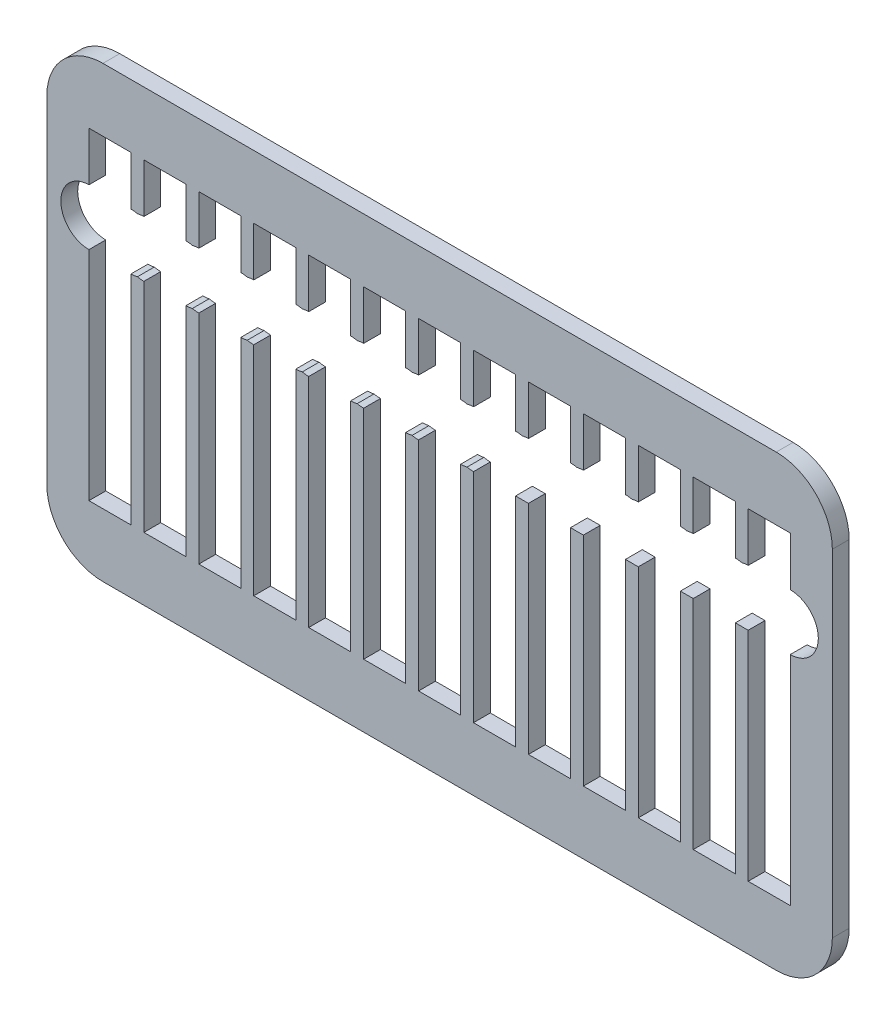
SolidWorks part; units mm, degrees
ref_plane "Front Plane" through (0, 0, 0) normal (0, 0, 1) x (1, 0, 0)
ref_plane "Top Plane" through (0, 0, 0) normal (0, 1, 0) x (1, 0, 0)
ref_plane "Right Plane" through (0, 0, 0) normal (1, 0, 0) x (0, 0, -1)
sketch "Sketch1" plane through (0, 0, 0) normal (0, 0, 1) x (1, 0, 0)
  line L1 (20, 0) -> (260, 0)
  line L2 (0, 20) -> (0, 140)
  line L3 (20, 160) -> (260, 160)
  line L4 (280, 20) -> (280, 140)
  arc A0 (260, 0) -> (280, 20) centre (260, 20) ccw
  arc A1 (260, 160) -> (280, 140) centre (260, 140) cw
  arc A2 (0, 140) -> (20, 160) centre (20, 140) cw
  arc A3 (20, 0) -> (0, 20) centre (20, 20) cw
  point P7 (280, 0)
  point P10 (280, 160)
  point P13 (0, 160)
  point P16 (0, 0)
  dimension "D3" = 20
  dimension "D1" = 280
  dimension "D2" = 160
extrude "Boss-Extrude1" add sketch "Sketch1" along normal blind 6
sketch "Sketch2" plane through (0, 0, 6) normal (0, 0, 1) x (1, 0, 0)
  line L0 (15, 137.5) -> (15, 160) construction
  line L1 (15, 137.5) -> (30, 137.5)
  line L2 (15, 137.5) -> (15, 120)
  line L3 (15, 22.5) -> (30, 22.5)
  line L4 (30, 137.5) -> (30, 120)
  line L5 (260, 160) -> (20, 160) construction
  line L6 (15, 22.5) -> (15, 0) construction
  line L7 (152.0833, 137.5) -> (152.0833, 120)
  line L8 (0, 110) -> (280, 110) construction
  line L9 (152.0833, 100) -> (152.0833, 22.5)
  line L10 (152.0833, 22.5) -> (167.0833, 22.5)
  line L11 (22.5, 22.5) -> (22.5, 37.2302) construction
  line L12 (15, 100) -> (15, 22.5)
  line L13 (30, 100) -> (30, 22.5)
  line L14 (34.5833, 137.5) -> (34.5833, 120)
  line L15 (34.5833, 100) -> (34.5833, 22.5)
  line L16 (34.5833, 22.5) -> (49.5833, 22.5)
  line L17 (49.5833, 100) -> (49.5833, 22.5)
  line L18 (49.5833, 137.5) -> (49.5833, 120)
  line L19 (34.5833, 137.5) -> (49.5833, 137.5)
  line L20 (54.1667, 137.5) -> (54.1667, 120)
  line L21 (54.1667, 100) -> (54.1667, 22.5)
  line L22 (54.1667, 22.5) -> (69.1667, 22.5)
  line L23 (69.1667, 100) -> (69.1667, 22.5)
  line L24 (69.1667, 137.5) -> (69.1667, 120)
  line L25 (54.1667, 137.5) -> (69.1667, 137.5)
  line L26 (73.75, 137.5) -> (73.75, 120)
  line L27 (73.75, 100) -> (73.75, 22.5)
  line L28 (73.75, 22.5) -> (88.75, 22.5)
  line L29 (88.75, 100) -> (88.75, 22.5)
  line L30 (88.75, 137.5) -> (88.75, 120)
  line L31 (73.75, 137.5) -> (88.75, 137.5)
  line L32 (93.3333, 137.5) -> (93.3333, 120)
  line L33 (93.3333, 100) -> (93.3333, 22.5)
  line L34 (93.3333, 22.5) -> (108.3333, 22.5)
  line L35 (108.3333, 100) -> (108.3333, 22.5)
  line L36 (108.3333, 137.5) -> (108.3333, 120)
  line L37 (93.3333, 137.5) -> (108.3333, 137.5)
  line L38 (112.9167, 137.5) -> (112.9167, 120)
  line L39 (112.9167, 100) -> (112.9167, 22.5)
  line L40 (112.9167, 22.5) -> (127.9167, 22.5)
  line L41 (127.9167, 100) -> (127.9167, 22.5)
  line L42 (127.9167, 137.5) -> (127.9167, 120)
  line L43 (112.9167, 137.5) -> (127.9167, 137.5)
  line L44 (132.5, 137.5) -> (132.5, 120)
  line L45 (132.5, 100) -> (132.5, 22.5)
  line L46 (132.5, 22.5) -> (147.5, 22.5)
  line L47 (147.5, 100) -> (147.5, 22.5)
  line L48 (147.5, 137.5) -> (147.5, 120)
  line L49 (132.5, 137.5) -> (147.5, 137.5)
  line L50 (15, 44.6954) -> (0, 44.6954) construction
  line L51 (0, 140) -> (0, 20) construction
  line L52 (280, 20) -> (280, 140) construction
  line L53 (167.0833, 100) -> (171.6667, 100)
  line L54 (167.0833, 100) -> (167.0833, 22.5)
  line L55 (167.0833, 137.5) -> (167.0833, 120)
  line L56 (152.0833, 137.5) -> (167.0833, 137.5)
  line L57 (171.6667, 137.5) -> (171.6667, 120)
  line L58 (171.6667, 100) -> (171.6667, 22.5)
  line L59 (171.6667, 22.5) -> (186.6667, 22.5)
  line L60 (186.6667, 100) -> (186.6667, 22.5)
  line L61 (186.6667, 137.5) -> (186.6667, 120)
  line L62 (171.6667, 137.5) -> (186.6667, 137.5)
  line L63 (191.25, 137.5) -> (191.25, 120)
  line L64 (191.25, 100) -> (191.25, 22.5)
  line L65 (191.25, 22.5) -> (206.25, 22.5)
  line L66 (206.25, 100) -> (206.25, 22.5)
  line L67 (206.25, 137.5) -> (206.25, 120)
  line L68 (191.25, 137.5) -> (206.25, 137.5)
  line L69 (210.8333, 137.5) -> (210.8333, 120)
  line L70 (210.8333, 100) -> (210.8333, 22.5)
  line L71 (210.8333, 22.5) -> (225.8333, 22.5)
  line L72 (225.8333, 100) -> (225.8333, 22.5)
  line L73 (225.8333, 137.5) -> (225.8333, 120)
  line L74 (210.8333, 137.5) -> (225.8333, 137.5)
  line L75 (230.4167, 137.5) -> (230.4167, 120)
  line L76 (230.4167, 100) -> (230.4167, 22.5)
  line L77 (230.4167, 22.5) -> (245.4167, 22.5)
  line L78 (245.4167, 100) -> (245.4167, 22.5)
  line L79 (245.4167, 137.5) -> (245.4167, 120)
  line L80 (230.4167, 137.5) -> (245.4167, 137.5)
  line L81 (250, 137.5) -> (250, 120)
  line L82 (250, 100) -> (250, 22.5)
  line L83 (250, 22.5) -> (265, 22.5)
  line L84 (265, 100) -> (265, 22.5)
  line L85 (265, 137.5) -> (265, 120)
  line L86 (250, 137.5) -> (265, 137.5)
  line L87 (186.6667, 100) -> (191.25, 100)
  line L88 (206.25, 100) -> (210.8333, 100)
  line L89 (225.8333, 100) -> (230.4167, 100)
  line L90 (245.4167, 100) -> (250, 100)
  arc A0 (30, 120) -> (32.2917, 119.7339) centre (30, 110) cw
  arc A1 (15, 120) -> (15, 100) centre (15, 110) ccw
  arc A2 (34.5833, 120) -> (32.2917, 119.7339) centre (34.5833, 110) ccw
  arc A3 (49.5833, 120) -> (51.875, 119.7339) centre (49.5833, 110) cw
  arc A4 (54.1667, 120) -> (51.875, 119.7339) centre (54.1667, 110) ccw
  arc A5 (69.1667, 120) -> (71.4583, 119.7339) centre (69.1667, 110) cw
  arc A6 (73.75, 120) -> (71.4583, 119.7339) centre (73.75, 110) ccw
  arc A7 (88.75, 120) -> (91.0417, 119.7339) centre (88.75, 110) cw
  arc A8 (93.3333, 120) -> (91.0417, 119.7339) centre (93.3333, 110) ccw
  arc A9 (108.3333, 120) -> (110.625, 119.7339) centre (108.3333, 110) cw
  arc A10 (112.9167, 120) -> (110.625, 119.7339) centre (112.9167, 110) ccw
  arc A11 (127.9167, 120) -> (130.2083, 119.7339) centre (127.9167, 110) cw
  arc A12 (132.5, 120) -> (130.2083, 119.7339) centre (132.5, 110) ccw
  arc A13 (147.5, 120) -> (149.7917, 119.7339) centre (147.5, 110) cw
  arc A14 (32.2917, 100.2661) -> (34.5833, 100) centre (34.5833, 110) ccw
  arc A15 (32.2917, 100.2661) -> (30, 100) centre (30, 110) cw
  arc A16 (51.875, 100.2661) -> (49.5833, 100) centre (49.5833, 110) cw
  arc A17 (51.875, 100.2661) -> (54.1667, 100) centre (54.1667, 110) ccw
  arc A18 (71.4583, 100.2661) -> (73.75, 100) centre (73.75, 110) ccw
  arc A19 (71.4583, 100.2661) -> (69.1667, 100) centre (69.1667, 110) cw
  arc A20 (91.0417, 100.2661) -> (93.3333, 100) centre (93.3333, 110) ccw
  arc A21 (91.0417, 100.2661) -> (88.75, 100) centre (88.75, 110) cw
  arc A22 (110.625, 100.2661) -> (112.9167, 100) centre (112.9167, 110) ccw
  arc A23 (110.625, 100.2661) -> (108.3333, 100) centre (108.3333, 110) cw
  arc A24 (130.2083, 100.2661) -> (127.9167, 100) centre (127.9167, 110) cw
  arc A25 (130.2083, 100.2661) -> (132.5, 100) centre (132.5, 110) ccw
  arc A26 (152.0833, 120) -> (149.7917, 119.7339) centre (152.0833, 110) ccw
  arc A27 (167.0833, 120) -> (169.375, 119.7339) centre (167.0833, 110) cw
  arc A28 (171.6667, 120) -> (169.375, 119.7339) centre (171.6667, 110) ccw
  arc A29 (186.6667, 120) -> (188.9583, 119.7339) centre (186.6667, 110) cw
  arc A30 (191.25, 120) -> (188.9583, 119.7339) centre (191.25, 110) ccw
  arc A31 (206.25, 120) -> (208.5417, 119.7339) centre (206.25, 110) cw
  arc A32 (210.8333, 120) -> (208.5417, 119.7339) centre (210.8333, 110) ccw
  arc A33 (225.8333, 120) -> (228.125, 119.7339) centre (225.8333, 110) cw
  arc A34 (230.4167, 120) -> (228.125, 119.7339) centre (230.4167, 110) ccw
  arc A35 (245.4167, 120) -> (247.7083, 119.7339) centre (245.4167, 110) cw
  arc A36 (250, 120) -> (247.7083, 119.7339) centre (250, 110) ccw
  arc A38 (149.7917, 100.2661) -> (152.0833, 100) centre (152.0833, 110) ccw
  arc A39 (149.7917, 100.2661) -> (147.5, 100) centre (147.5, 110) cw
  arc A40 (265, 100) -> (265, 120) centre (265, 110) ccw
  arc A41 (265, 120) -> (267.2917, 119.7339) centre (265, 110) cw [skipped]
  dimension "D3" = 10
  dimension "D1" = 15
  dimension "D2" = 115
  dimension "D4" = 50
  dimension "D6" = 15
  dimension "D7" = 15
  dimension "D5" = 13
extrude "Cut-Extrude1" cut sketch "Sketch2" against normal blind 6
